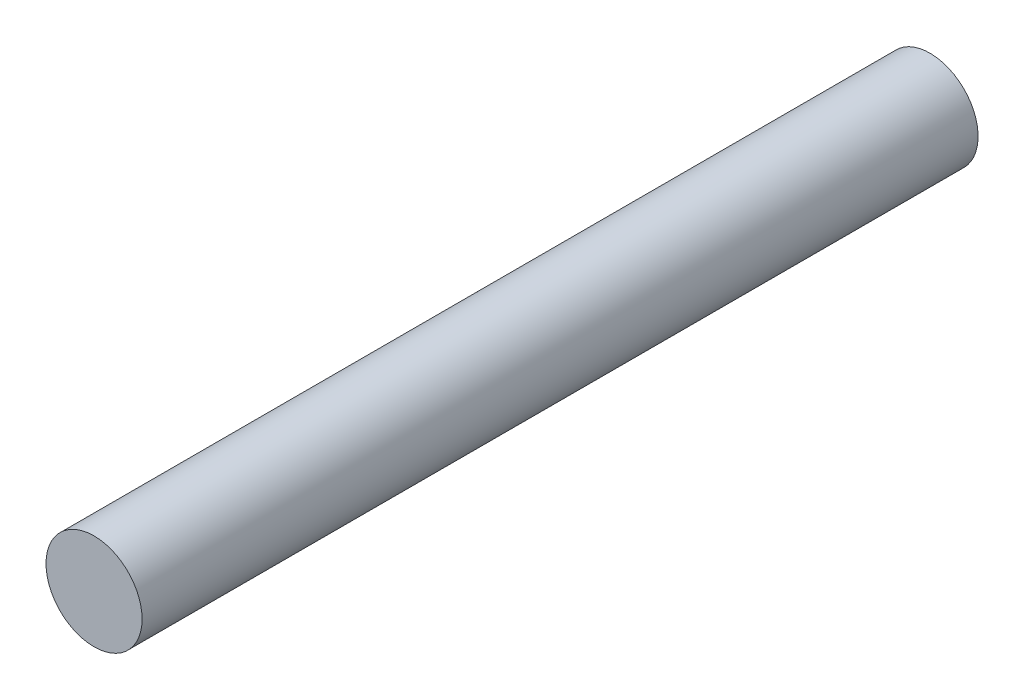
SolidWorks part; units mm, degrees
material "1060 Alloy"
ref_plane "Front Plane" through (0, 0, 0) normal (0, 0, 1) x (1, 0, 0)
ref_plane "Top Plane" through (0, 0, 0) normal (0, 1, 0) x (1, 0, 0)
ref_plane "Right Plane" through (0, 0, 0) normal (1, 0, 0) x (0, 0, -1)
sketch "Sketch1" plane through (0, 0, 0) normal (0, 0, 1) x (1, 0, 0)
  circle A0 centre (0, 0) radius 3
  dimension "D1" = 6
extrude "Boss-Extrude1" add sketch "Sketch1" along normal mid plane 100
sketch "Sketch2" plane through (0, 0, 50) normal (0, 0, 1) x (1, 0, 0)
  circle A1 centre (0, 0) radius 3
  circle A2 centre (0, 0) radius 3
  dimension "D1" = 0
extrude "Cut-Extrude1" cut sketch "Sketch2" against normal up to surface (27.65 mm away)
sketch "Sketch3" plane through (0, 0, -50) normal (0, 0, -1) x (-1, 0, 0)
  circle A1 centre (0, 0) radius 3
  circle A2 centre (0, 0) radius 3
  dimension "D1" = 0
extrude "Cut-Extrude2" cut sketch "Sketch3" against normal offset from surface (20.15 mm away) 7.5
